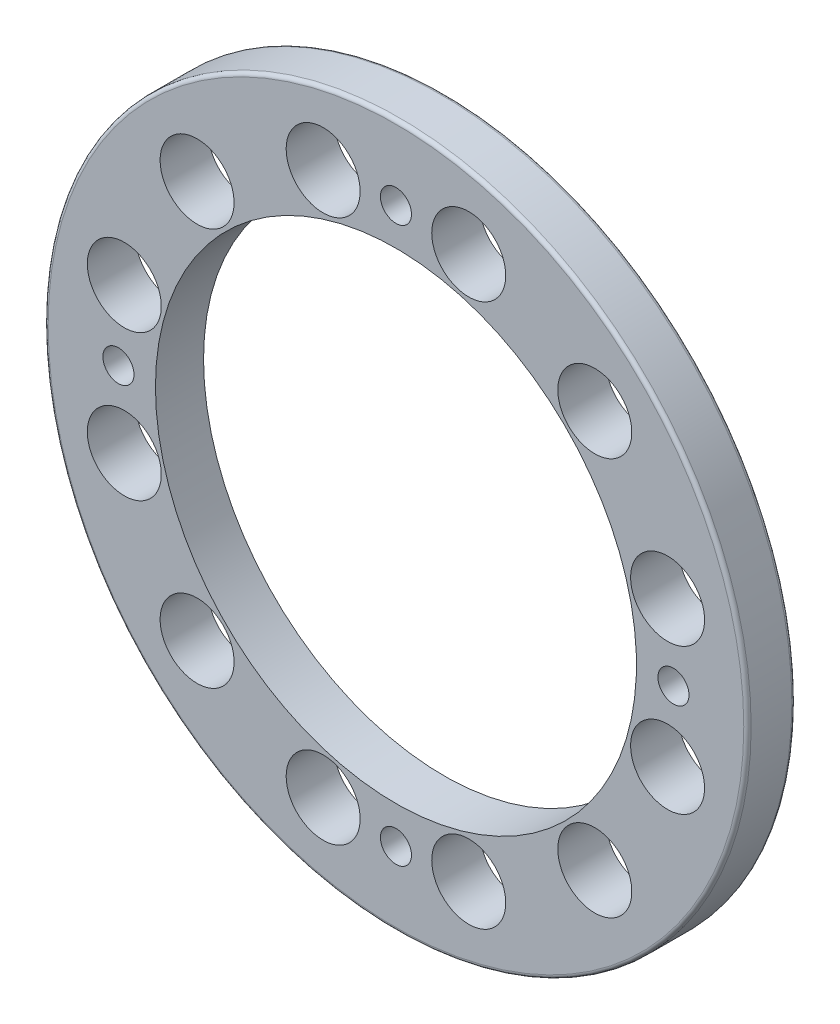
SolidWorks part; units mm, degrees
ref_plane "Front Plane" through (0, 0, 0) normal (0, 0, 1) x (1, 0, 0)
ref_plane "Top Plane" through (0, 0, 0) normal (0, 1, 0) x (1, 0, 0)
ref_plane "Right Plane" through (0, 0, 0) normal (1, 0, 0) x (0, 0, -1)
sketch "Sketch1" plane through (0, 0, 0) normal (0, 0, 1) x (1, 0, 0)
  circle A0 centre (0, 0) radius 47.5
  circle A1 centre (0, 0) radius 32.5
  dimension "D1" = 95
  dimension "D2" = 65
extrude "Boss-Extrude1" add sketch "Sketch1" along normal blind 6.5
sketch "Sketch2" plane through (0, 0, 0) normal (0, 0, 1) x (1, 0, 0)
  line L0 (0, 0) -> (9.8351, 36.7052) construction
  line L1 (9.8351, 36.7052) -> (11.1292, 41.5348) construction
  line L2 (11.1292, 41.5348) -> (12.2939, 45.8815) construction
  line L3 (0, 0) -> (0, 47.5) construction
  circle A0 centre (0, 0) radius 38 construction
  circle A3 centre (9.8351, 36.7052) radius 5
  circle A4 centre (0, 0) radius 47.5 construction
  circle A5 centre (26.8701, 26.8701) radius 5
  circle A6 centre (36.7052, 9.8351) radius 5
  circle A7 centre (36.7052, -9.8351) radius 5
  circle A8 centre (26.8701, -26.8701) radius 5
  circle A9 centre (9.8351, -36.7052) radius 5
  circle A10 centre (-9.8351, -36.7052) radius 5
  circle A11 centre (-26.8701, -26.8701) radius 5
  circle A12 centre (-36.7052, -9.8351) radius 5
  circle A13 centre (-36.7052, 9.8351) radius 5
  circle A14 centre (-26.8701, 26.8701) radius 5
  circle A15 centre (-9.8351, 36.7052) radius 5
  point P37 (0, 0)
  dimension "D1" = 10
  dimension "D2" = 4.5
  dimension "D4" = 15
  dimension "D3" = 12
extrude "Cut-Extrude1" cut sketch "Sketch2" along normal through all
sketch "Sketch3" plane through (0, 0, 0) normal (0, 0, 1) x (1, 0, 0)
  line L0 (0, 0) -> (0, 32.5) construction
  line L1 (0, 32.5) -> (0, 35.5) construction
  line L2 (0, 39.5) -> (0, 47.5) construction
  line L3 (0, 35.5) -> (0, 37.5) construction
  circle A0 centre (0, 0) radius 32.5 construction
  circle A1 centre (0, 37.5) radius 2 construction
  circle A2 centre (0, 0) radius 47.5 construction
  circle A3 centre (37.5, 0) radius 2 construction
  circle A4 centre (0, -37.5) radius 2 construction
  circle A5 centre (-37.5, 0) radius 2 construction
  point P11 (0, 0)
  point P13 (0, 0)
  point P21 (0, 0)
  dimension "D1" = 8
  dimension "D3" = 4
  dimension "D2" = 3
hole_wizard "M5x0.8 Tapped Hole1" positions "Sketch4" profile "Sketch5" tap size "M5x0.8" standard "ANSI Metric" end condition through all
sketch "Sketch4" plane through (0, 0, 6.5) normal (0, 0, 1) x (1, 0, 0)
  point P0 (0, 37.5)
  point P3 (-37.5, 0)
  point P6 (37.5, 0)
  point P9 (0, -37.5)
sketch "Sketch5" plane through (0, 37.5, 6.5) normal (1, 0, 0) x (0, -1, 0)
  line L0 (0, 0) -> (0, 6.5)
  line L1 (0, 6.5) -> (2.1, 6.5)
  line L2 (2.1, 6.5) -> (2.1, 0)
  line L5 (2.1, 0) -> (0, 0)
  line L11 (0, -6.35) -> (0, 107.95) construction
  dimension "Thru Tap Drill Dia." = 4.2
  dimension "Thru Tap Drill Depth" = 6.5
cosmetic thread "Hole Thread1" parameters "D2"=5
cosmetic thread "Hole Thread2" parameters "D2"=5
cosmetic thread "Hole Thread3" parameters "D2"=5
cosmetic thread "Hole Thread4" parameters "D2"=5
fillet "Fillet1" radius 0.5 2 edges at (47.5, 0, 0) (47.5, 0, 6.5)
